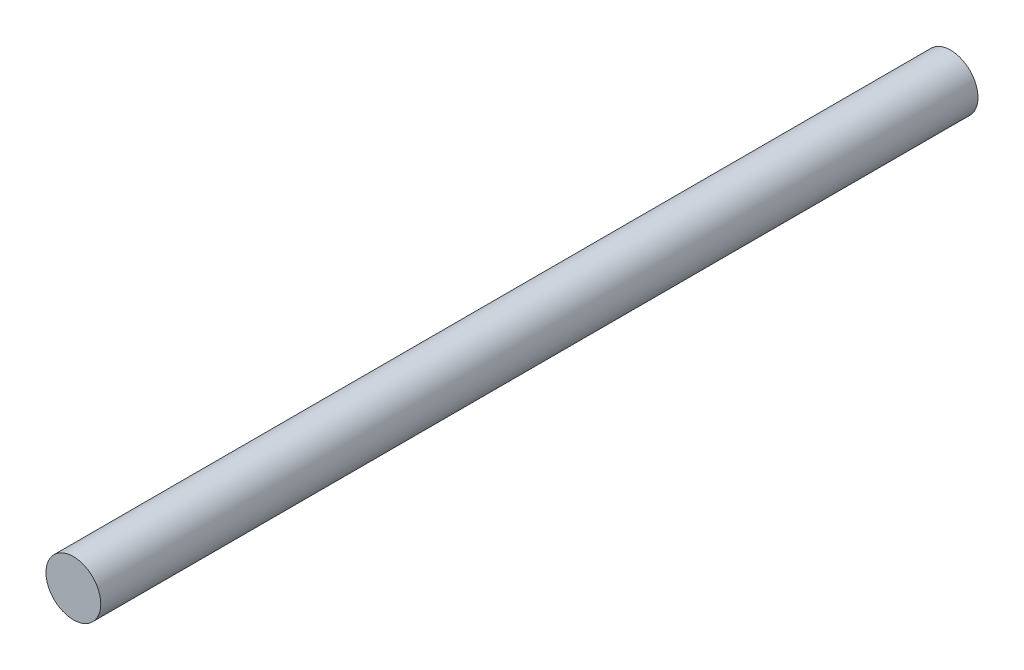
SolidWorks part; units mm, degrees
material "ABS PC"
ref_plane "Front Plane" through (0, 0, 0) normal (0, 0, 1) x (1, 0, 0)
ref_plane "Top Plane" through (0, 0, 0) normal (0, 1, 0) x (1, 0, 0)
ref_plane "Right Plane" through (0, 0, 0) normal (1, 0, 0) x (0, 0, -1)
sketch "Sketch1" plane through (0, 0, 0) normal (0, 0, 1) x (1, 0, 0)
  circle A0 centre (0, 0) radius 1
  dimension "D1" = 2
extrude "Boss-Extrude1" add sketch "Sketch1" along normal blind 32
